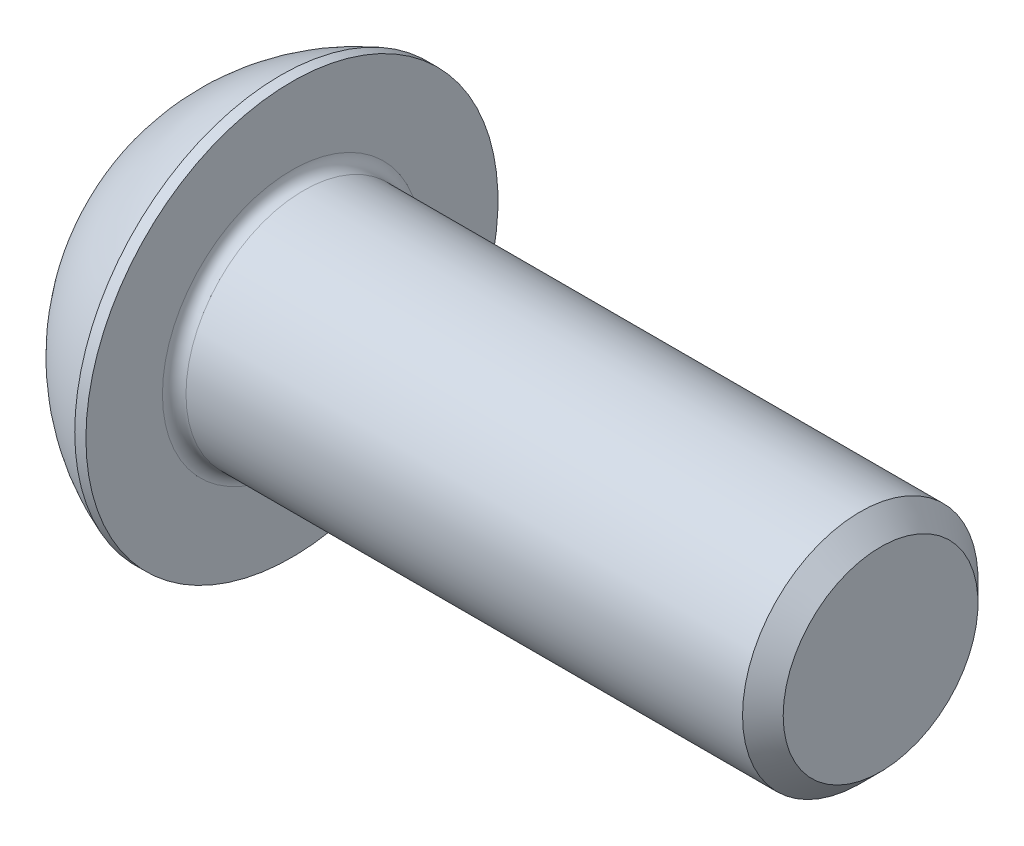
SolidWorks part; units mm, degrees
ref_plane "Plane1" through (0, 0, 0) normal (0, 0, 1) x (1, 0, 0)
ref_plane "Plane2" through (0, 0, 0) normal (0, 1, 0) x (1, 0, 0)
ref_plane "Plane3" through (0, 0, 0) normal (1, 0, 0) x (0, 0, -1)
other "Configuration Table"
sketch "BodySke" plane through (0, 0, 0) normal (0, 0, 1) x (1, 0, 0)
  line L0 (24.4, 0) -> (24.4, 3.3095)
  line L1 (23.7095, 4) -> (4.4, 4)
  line L2 (4.4, 4) -> (4.4, 7)
  line L3 (4.4, 7) -> (4.02, 7)
  line L4 (0, 0) -> (101.6, 0) construction
  line L5 (4.4, -7) -> (4.02, -7) construction
  line L6 (55.6768, -4) -> (4.4, -4) construction
  line L7 (24.4, 0) -> (0, 0)
  line L8 (0, 3.5) -> (0, -3.5) construction
  line L9 (0, 0) -> (0, 3.5)
  line L10 (24.4, 3.3095) -> (23.7095, 4)
  line L11 (24.4, -3.3095) -> (23.7095, -4) construction
  line L12 (5.65, 9.525) -> (5.65, -4) construction
  line L13 (4.4, 9.525) -> (4.4, -4) construction
  arc A1 (0, 3.5) -> (4.02, 7) centre (6.5809, 0) cw
  dimension "Head_side_ht" = 0.38
  dimension "Body_ch_ang" = 45
revolve "BaseBody" add sketch "BodySke" angle 360 about L4
cosmetic thread "ThreadCosmetic" [suppressed] parameters "Thread_length"=17.5, "Thread_minor"=6.619
fillet "Fillet1" radius 0.4 1 edges at (4.4, 0, 4)
sketch "Sketch2" plane through (0, 0, 0) normal (0, 0, 1) x (1, 0, 0)
  line L0 (0, 2.5) -> (2.6, 2.5)
  line L1 (2.6, 2.5) -> (4.0434, 0)
  line L3 (4.0434, 0) -> (0, 0)
  line L4 (0, 0) -> (0, 2.5)
  line L5 (0, -2.5) -> (2.6, -2.5) construction
  line L6 (0, 0) -> (47.625, 0) construction
  dimension "D2" = 60
  dimension "PreBroach_depth" = 2.6
  dimension "PreBroach_dia" = 5
revolve "PreBroach" cut sketch "Sketch2" angle 360 about L6
sketch "Sketch3" plane through (0, 0, 0) normal (1, 0, 0) x (0, 0, -1)
  line L0 (-2.5, -1.4434) -> (-2.5, 1.4434)
  line L1 (-2.5, 1.4434) -> (0, 2.8868)
  line L2 (0, 2.8868) -> (2.5, 1.4434)
  line L3 (2.5, 1.4434) -> (2.5, -1.4434)
  line L4 (2.5, -1.4434) -> (0, -2.8868)
  line L5 (0, -2.8868) -> (-2.5, -1.4434)
extrude "Hex" cut sketch "Sketch3" along normal blind 2.6
sketch "ThdSchSke" plane through (0, 0, 0) normal (0, 0, 1) x (1, 0, 0)
  line L0 (6.9, -3.3095) -> (6.4165, -4)
  line L1 (6.9, -3.3095) -> (7.3835, -4)
  line L2 (7.3835, -4) -> (7.3835, -5)
  line L3 (-3.175, 0) -> (5.1513, 0) construction
  line L5 (7.3835, -5) -> (6.4165, -5)
  line L6 (6.4165, -5) -> (6.4165, -4)
  dimension "SideAngle" = 55
  dimension "VeeAngle" = 70
revolve "ThreadSchematic" [suppressed] cut sketch "ThdSchSke" angle 360 about L3
pattern_linear "ThdSchPat" [suppressed]
equation "\"D1@BodySke\" = \"Head_dia@BodySke\" * .5"
equation "\"Thread_minor@ThreadCosmetic\" = \"Minor_dia@BodySke\""
equation "\"D1@Sketch3\" = \"Hex_size@Sketch3\" / 2"
equation "\"D2@Sketch3\" = \"D1@Sketch3\""
equation "\"D3@Sketch3\" = \"Hex_size@Sketch3\""
equation "\"Thread_length@ThreadCosmetic\" = ((sgn( (\"Length@BodySke\" - \"Advance@BodySke\" * 2.0) - \"Thread_nom@BodySke\" )-1)*( (\"Length@BodySke\" - \"Advance@BodySke\" * 2.0) - \"Thread_nom@BodySke\" ))/-2+ \"Thread_nom@BodySke\""
equation "\"Thread_minor@ThdSchSke\" = \"Minor_dia@BodySke\""
equation "\"Diameter@ThdSchSke\" = \"Diameter@BodySke\""
equation "\"Overcut@ThdSchSke\" = \"Diameter@BodySke\" * 1.25"
equation "\"Start@ThdSchSke\" = \"Head_ht@BodySke\" + \"Length@BodySke\" - \"Thread_length@ThreadCosmetic\"  '---Non-countersunk---"
equation "\"Num_threads@ThdSchPat\" = int( \"Thread_length@ThreadCosmetic\" / \"Advance@BodySke\" + 0.999 )  + 1"
equation "\"Advance@ThdSchPat\" = \"Thread_length@ThreadCosmetic\" /  (\"Num_threads@ThdSchPat\" - 1) 'relax it"
equation "\"Num_threads@ThdSchPat\" = \"Num_threads@ThdSchPat\" - sgn( \"Num_threads@ThdSchPat\" - 1) '---chamfered tips only---"
